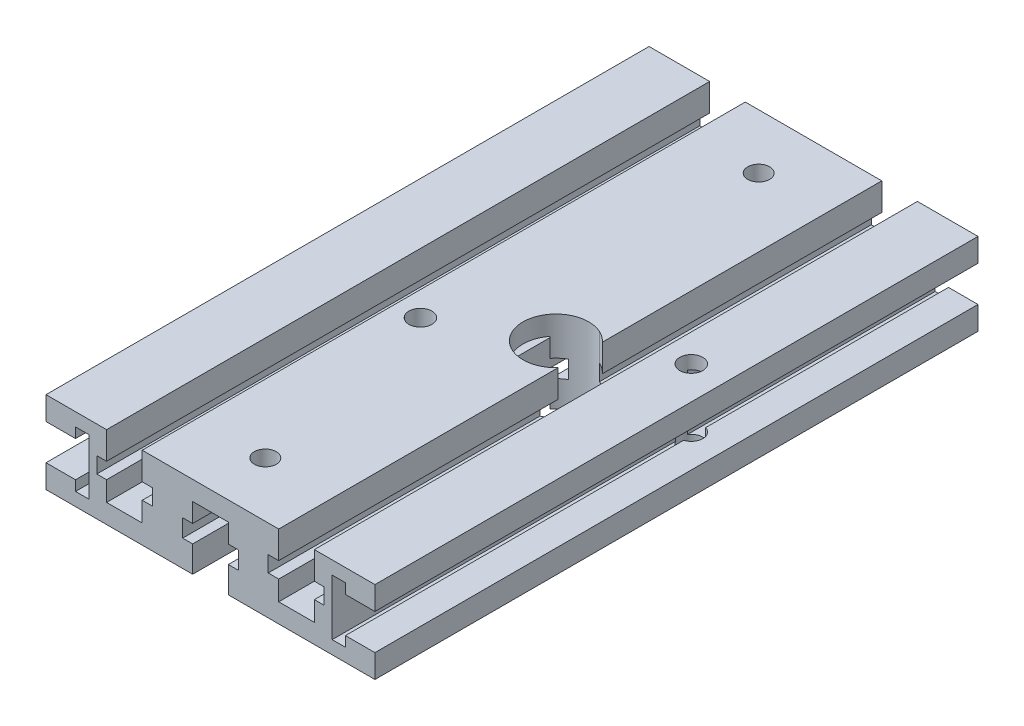
SolidWorks part; units mm, degrees
ref_plane "前视" through (0, 0, 0) normal (0, 0, 1) x (1, 0, 0)
ref_plane "上视" through (0, 0, 0) normal (0, 1, 0) x (1, 0, 0)
ref_plane "右视" through (0, 0, 0) normal (1, 0, 0) x (0, 0, -1)
sketch "草图1" plane through (0, 0, 0) normal (0, 0, 1) x (1, 0, 0)
  line L0 (0, 0) -> (26.75, 0)
  line L1 (0, 0) -> (0, 4.25)
  line L2 (0, 4.25) -> (5.3867, 4.25)
  line L3 (5.3867, 4.25) -> (5.3867, 2.4)
  line L4 (5.3867, 2.4) -> (7.8, 2.4)
  line L5 (7.8, 2.4) -> (7.8, 12.6)
  line L6 (7.8, 12.6) -> (5.3867, 12.6)
  line L7 (5.3867, 12.6) -> (5.3867, 10.75)
  line L8 (5.3867, 10.75) -> (0, 10.75)
  line L9 (0, 10.75) -> (0, 15)
  line L10 (0, 15) -> (11.0524, 15)
  line L11 (11.0524, 15) -> (11.0524, 10.0038)
  line L12 (11.0524, 10.0038) -> (9.2662, 10.0038)
  line L13 (9.2662, 10.0038) -> (9.2662, 7.0947)
  line L14 (9.2662, 7.0947) -> (11.0524, 7.0947)
  line L15 (11.0524, 7.0947) -> (11.0524, 3.5)
  line L16 (11.0524, 3.5) -> (17.5524, 3.5)
  line L17 (17.5524, 3.5) -> (17.5524, 7.0947)
  line L18 (17.5524, 7.0947) -> (19.4662, 7.0947)
  line L19 (19.4662, 7.0947) -> (19.4662, 10.0038)
  line L20 (19.4662, 10.0038) -> (17.5524, 10.0038)
  line L21 (17.5524, 10.0038) -> (17.5524, 15)
  line L22 (17.5524, 15) -> (30, 15)
  line L23 (26.75, 0) -> (26.75, 4.7964)
  line L24 (26.75, 4.7964) -> (24.9265, 4.7964)
  line L25 (24.9265, 4.7964) -> (24.9265, 8.0234)
  line L26 (24.9265, 8.0234) -> (26.75, 8.0234)
  line L27 (26.75, 8.0234) -> (26.75, 11.5)
  line L28 (26.75, 11.5) -> (30, 11.5)
  line L29 (30, 15) -> (42.4476, 15)
  line L30 (30, 11.5) -> (33.25, 11.5)
  line L32 (33.25, 8.0234) -> (33.25, 11.5)
  line L33 (35.0735, 8.0234) -> (33.25, 8.0234)
  line L34 (35.0735, 4.7964) -> (35.0735, 8.0234)
  line L35 (33.25, 4.7964) -> (35.0735, 4.7964)
  line L36 (33.25, 0) -> (33.25, 4.7964)
  line L37 (42.4476, 10.0038) -> (42.4476, 15)
  line L38 (40.5338, 10.0038) -> (42.4476, 10.0038)
  line L39 (40.5338, 7.0947) -> (40.5338, 10.0038)
  line L40 (42.4476, 7.0947) -> (40.5338, 7.0947)
  line L41 (42.4476, 3.5) -> (42.4476, 7.0947)
  line L42 (48.9476, 3.5) -> (42.4476, 3.5)
  line L43 (48.9476, 7.0947) -> (48.9476, 3.5)
  line L44 (50.7338, 7.0947) -> (48.9476, 7.0947)
  line L45 (50.7338, 10.0038) -> (50.7338, 7.0947)
  line L46 (48.9476, 10.0038) -> (50.7338, 10.0038)
  line L47 (48.9476, 15) -> (48.9476, 10.0038)
  line L48 (60, 15) -> (48.9476, 15)
  line L49 (60, 10.75) -> (60, 15)
  line L50 (54.6133, 10.75) -> (60, 10.75)
  line L51 (54.6133, 12.6) -> (54.6133, 10.75)
  line L52 (52.2, 12.6) -> (54.6133, 12.6)
  line L53 (52.2, 2.4) -> (52.2, 12.6)
  line L54 (54.6133, 2.4) -> (52.2, 2.4)
  line L55 (54.6133, 4.25) -> (54.6133, 2.4)
  line L56 (60, 4.25) -> (54.6133, 4.25)
  line L57 (60, 0) -> (60, 4.25)
  line L58 (60, 0) -> (33.25, 0)
  dimension "D1" = 6.5
  dimension "D2" = 7.8
  dimension "D3" = 15
  dimension "D4" = 6.5
  dimension "D5" = 11.5
  dimension "D6" = 2.4
  dimension "D7" = 10.2
  dimension "D8" = 15
  dimension "D9" = 2.4
  dimension "D10" = 4.25
  dimension "D11" = 11.5
  dimension "D12" = 60
  dimension "D13" = 3.25
extrude "凸台-拉伸1" add sketch "草图1" along normal blind 110
hole_wizard "Ø4.0 (4) 直径孔1" positions "草图5" profile "草图4" hole size "Ø4.0" standard "Gb" end condition through all
sketch "草图5" plane through (0, 11.5, 0) normal (0, -1, 0) x (-1, 0, 0)
  line L0 (0, -110) -> (0, 0) construction
  line L2 (-26.75, -110) -> (-33.25, -110) construction
  line L3 (-26.75, 0) -> (-33.25, 0) construction
  point P0 (-30, -100)
  point P2 (-30, -10)
  dimension "D1" = 30
  dimension "D2" = 10
  dimension "D3" = 10
sketch "草图4" plane through (30, 11.5, 100) normal (1, 0, 0) x (0, 0, -1)
  line L0 (0, 0) -> (0, 3.5)
  line L1 (0, 3.5) -> (2, 3.5)
  line L2 (2, 3.5) -> (2, 0)
  line L5 (2, 0) -> (0, 0)
  line L11 (0, -6.35) -> (0, 107.95) construction
  dimension "通孔孔直径" = 4
  dimension "通孔孔深度" = 3.5
hole_wizard "Ø12.0 (12) 直径孔1" positions "草图7" profile "草图6" hole size "Ø12.0" standard "Gb" end condition through all
sketch "草图7" plane through (0, 0, 0) normal (0, -1, 0) x (-1, 0, 0)
  line L3 (-33.25, -110) -> (-60, -110) construction
  line L6 (-60, -110) -> (-60, 0) construction
  point P0 (-38, -55)
  dimension "D1" = 55
  dimension "D2" = 22
sketch "草图6" plane through (38, 0, 55) normal (1, 0, 0) x (0, 0, -1)
  line L0 (0, 0) -> (0, 15)
  line L1 (0, 15) -> (6, 15)
  line L2 (6, 15) -> (6, 0)
  line L5 (6, 0) -> (0, 0)
  line L11 (0, -6.35) -> (0, 107.95) construction
  dimension "通孔孔直径" = 12
  dimension "通孔孔深度" = 15
hole_wizard "M5 螺纹孔1" positions "草图9" profile "草图8" tap size "M5" standard "Gb" end condition through all
sketch "草图9" plane through (0, 0, 0) normal (0, -1, 0) x (-1, 0, 0)
  line L0 (-33.25, -110) -> (-60, -110) construction
  line L1 (-60, -110) -> (-60, 0) construction
  line L2 (0, -110) -> (-26.75, -110) construction
  line L3 (0, -110) -> (0, 0) construction
  point P0 (-54, -46.3)
  point P2 (-22, -63.7)
  dimension "D1" = 63.7
  dimension "D2" = 6
  dimension "D3" = 46.3
  dimension "D4" = 22
sketch "草图8" plane through (54, 0, 46.3) normal (1, 0, 0) x (0, 0, -1)
  line L0 (0, 0) -> (0, 15)
  line L1 (0, 15) -> (2.1, 15)
  line L2 (2.1, 15) -> (2.1, 0)
  line L5 (2.1, 0) -> (0, 0)
  line L11 (0, -6.35) -> (0, 107.95) construction
  dimension "通孔螺纹孔钻头直径" = 4.2
  dimension "通孔螺纹孔钻头深度" = 15
cosmetic thread "孔螺蚊线1" parameters "D2"=5
cosmetic thread "孔螺蚊线2" parameters "D2"=5
